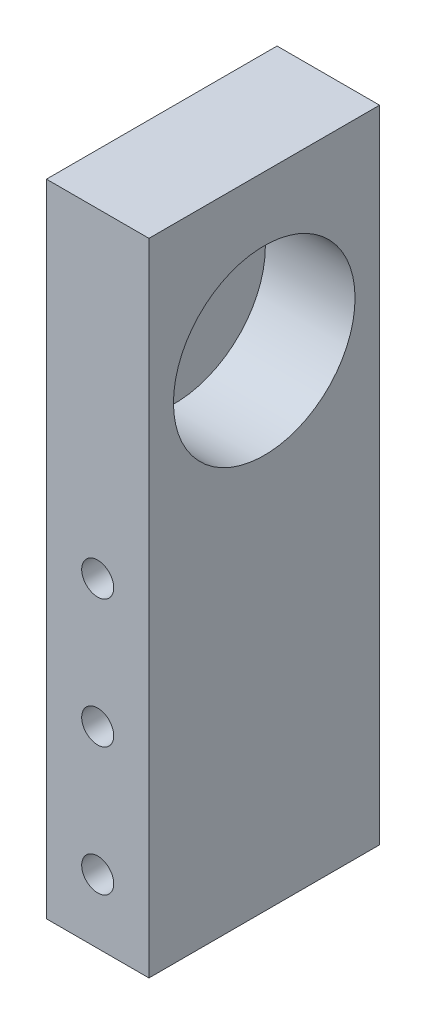
SolidWorks part; units mm, degrees
ref_plane "Front Plane" through (0, 0, 0) normal (0, 0, 1) x (1, 0, 0)
ref_plane "Top Plane" through (0, 0, 0) normal (0, 1, 0) x (1, 0, 0)
ref_plane "Right Plane" through (0, 0, 0) normal (1, 0, 0) x (0, 0, -1)
sketch "Sketch1" plane through (0, 0, 0) normal (0, 0, 1) x (1, 0, 0)
  line L1 (0, 0) -> (20.32, 0)
  line L2 (0, 0) -> (0, 76.2)
  line L3 (0, 76.2) -> (20.32, 76.2)
  line L4 (20.32, 0) -> (20.32, 76.2)
  dimension "D1" = 76.2
  dimension "D2" = 20.32
extrude "Boss-Extrude1" add sketch "Sketch1" along normal mid plane 45.72
sketch "Sketch2" plane through (0, 0, 22.86) normal (0, 0, 1) x (1, 0, 0)
  line L0 (0, 0) -> (20.32, 0) construction
  line L1 (20.32, 76.2) -> (0, 76.2) construction
  line L2 (0, 76.2) -> (0, 0) construction
  circle A0 centre (10.16, 12.7) radius 3.175
  circle A1 centre (10.16, 38.1) radius 3.175
  circle A2 centre (10.16, 63.5) radius 3.175
  dimension "D1" = 6.35
  dimension "D2" = 10.16
  dimension "0.25" = 6.35
  dimension "D3" = 6.35
  dimension "D4" = 25.4
  dimension "D5" = 25.4
  dimension "D6" = 12.7
  dimension "D7" = 12.7
extrude "Cut-Extrude1" cut sketch "Sketch2" against normal through all
sketch "Sketch3" plane through (0, 76.2, 0) normal (0, 1, 0) x (1, 0, 0)
  line L1 (0, 22.86) -> (20.32, 22.86)
  line L2 (0, 22.86) -> (0, -22.86)
  line L3 (0, -22.86) -> (20.32, -22.86)
  line L4 (20.32, 22.86) -> (20.32, -22.86)
extrude "Boss-Extrude2" add sketch "Sketch3" along normal blind 50.8
sketch "Sketch4" plane through (20.32, 0, 0) normal (1, 0, 0) x (0, 0, -1)
  line L0 (-22.86, 127) -> (22.86, 127) construction
  circle A0 centre (0, 96.3) radius 18
  dimension "D1" = 35.9999
  dimension "D2" = 30.7
extrude "Cut-Extrude2" cut sketch "Sketch4" against normal blind 17.78
sketch "Sketch5" plane through (2.54, 0, 0) normal (1, 0, 0) x (0, 0, -1)
  circle A0 centre (0, 96.3) radius 3
extrude "Cut-Extrude3" cut sketch "Sketch5" against normal through all
